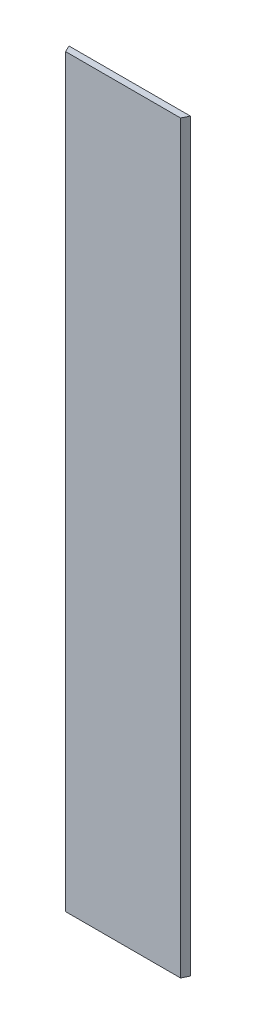
SolidWorks part; units mm, degrees
ref_plane "Front Plane" through (0, 0, 0) normal (0, 0, 1) x (1, 0, 0)
ref_plane "Top Plane" through (0, 0, 0) normal (0, 1, 0) x (1, 0, 0)
ref_plane "Right Plane" through (0, 0, 0) normal (1, 0, 0) x (0, 0, -1)
sketch "Sketch1" plane through (0, 0, 0) normal (0, 1, 0) x (1, 0, 0)
  line L0 (-12.7, -26.4729) -> (12.7, -26.4729) construction
  line L1 (-41.6101, -23.2979) -> (41.6101, -23.2979)
  line L2 (-43.939, -18.5354) -> (43.939, -18.5354)
  circle A0 centre (0, 0) radius 47.6885 construction
  circle A1 centre (-12.7, -31.2354) radius 4.7625 construction
  circle A2 centre (12.7, -31.2354) radius 4.7625 construction
  circle A3 centre (12.7, -31.2354) radius 12.7 construction
  circle A4 centre (12.7, -31.2354) radius 13.97 construction
  circle A5 centre (-12.7, -31.2354) radius 12.7 construction
  circle A6 centre (-12.7, -31.2354) radius 13.97 construction
  arc A7 (-41.6101, -23.2979) -> (-43.939, -18.5354) centre (0, 0) cw
  arc A8 (41.6101, -23.2979) -> (43.939, -18.5354) centre (0, 0) ccw
  dimension "D1" = 95.377
  dimension "D2" = 27.94
  dimension "D3" = 25.4
  dimension "D4" = 9.525
  dimension "D5" = 3.175
  dimension "D6" = 4.7625
extrude "Boss-Extrude1" add sketch "Sketch1" along normal blind 539.75
